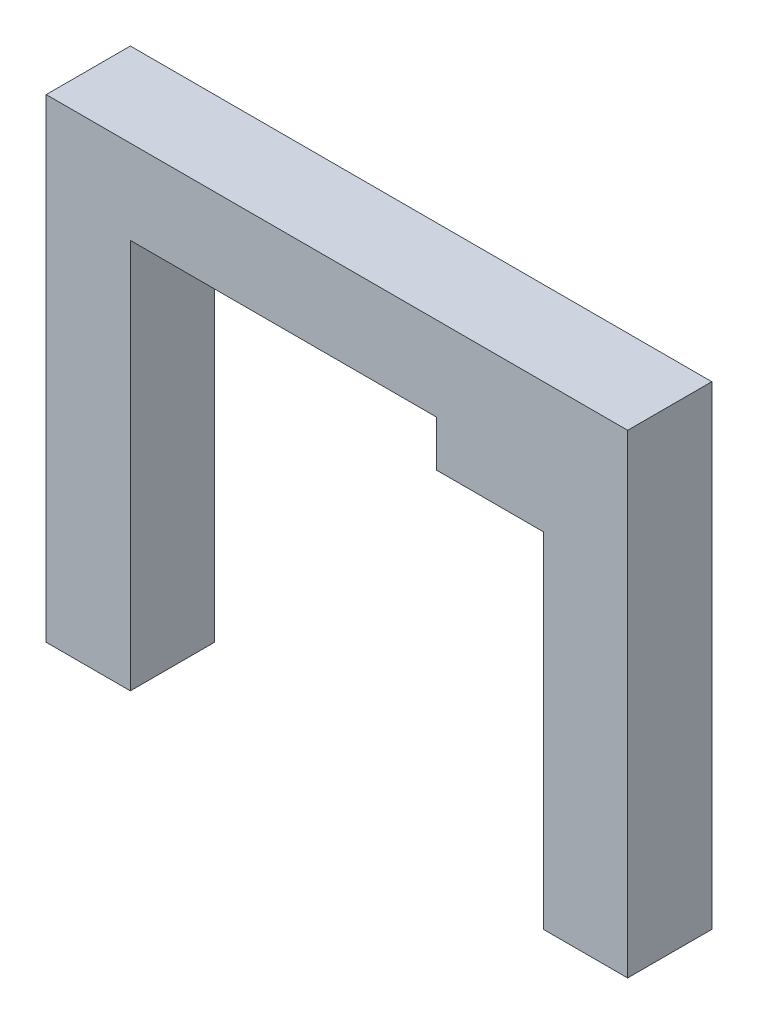
SolidWorks part; units mm, degrees
material "ﾁｰｸ材"
ref_plane "正面" through (0, 0, 0) normal (0, 0, 1) x (1, 0, 0)
ref_plane "平面" through (0, 0, 0) normal (0, 1, 0) x (1, 0, 0)
ref_plane "右側面" through (0, 0, 0) normal (1, 0, 0) x (0, 0, -1)
sketch "ｽｹｯﾁ1" plane through (0, 0, 0) normal (0, 0, 1) x (1, 0, 0)
  line L0 (0, 0) -> (0, 25.5)
  line L1 (0, 0) -> (-5.5, 0)
  line L2 (-5.5, 0) -> (-5.5, 31)
  line L3 (-5.5, 31) -> (32.5, 31)
  line L4 (32.5, 31) -> (32.5, 0)
  line L5 (32.5, 0) -> (27, 0)
  line L9 (27, 22.5) -> (20, 22.5)
  line L10 (20, 22.5) -> (20, 25.5)
  line L11 (20, 25.5) -> (0, 25.5)
  line L12 (27, 22.5) -> (27, 0)
  dimension "D1" = 20
  dimension "D2" = 25.5
  dimension "D3" = 5.5
  dimension "D4" = 5.5
  dimension "D5" = 5.5
  dimension "D6" = 3
  dimension "D7" = 7
extrude "ﾎﾞｽ - 押し出し1" add sketch "ｽｹｯﾁ1" along normal blind 5.5
